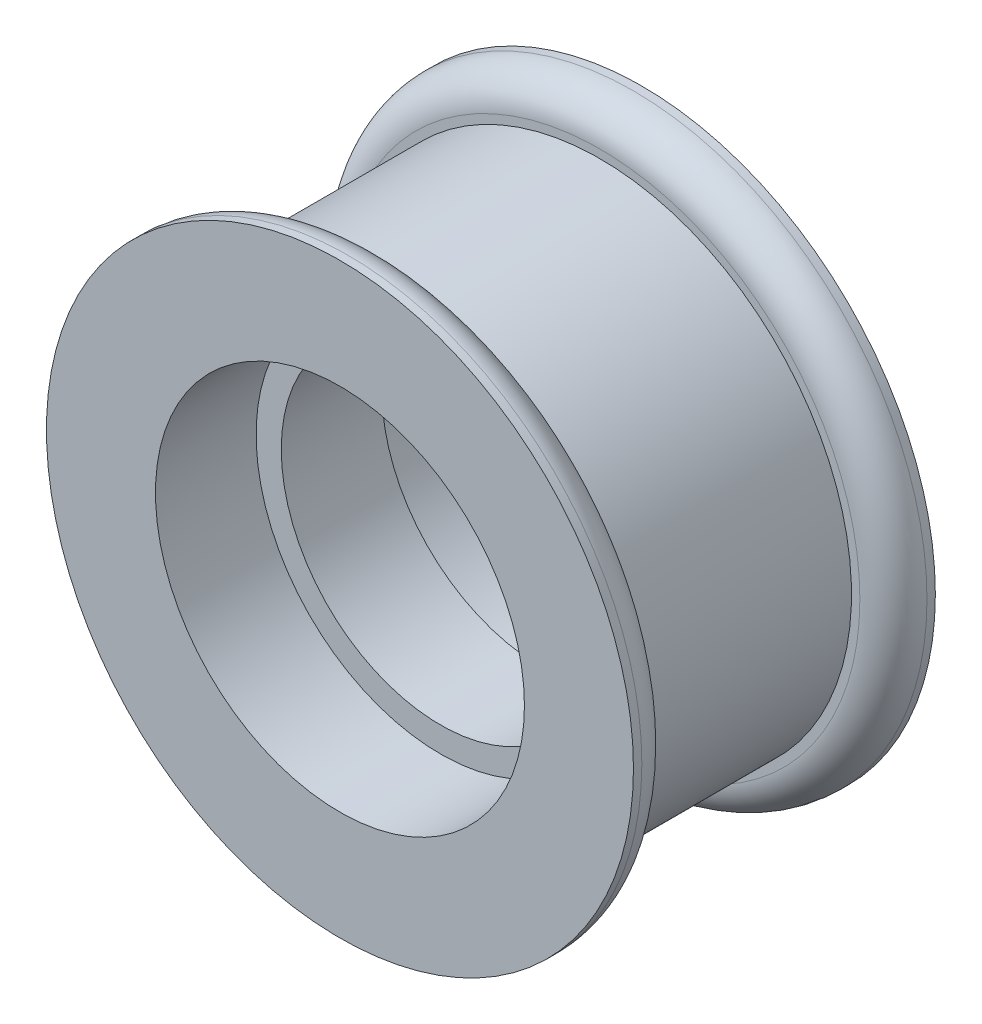
SolidWorks part; units mm, degrees
material "AISI 304"
ref_plane "前视基准面" through (0, 0, 0) normal (0, 0, 1) x (1, 0, 0)
ref_plane "上视基准面" through (0, 0, 0) normal (0, 1, 0) x (1, 0, 0)
ref_plane "右视基准面" through (0, 0, 0) normal (1, 0, 0) x (0, 0, -1)
sketch "草图1" plane through (0, 0, 0) normal (0, 0, 1) x (1, 0, 0)
  circle A0 centre (0, 0) radius 15
  dimension "D1" = 30
extrude "拉伸1" add sketch "草图1" along normal mid plane 13
sketch "草图2" plane through (0, 0, 6.5) normal (0, 0, 1) x (1, 0, 0)
  circle A0 centre (0, 0) radius 17.5
  dimension "D1" = 35
extrude "拉伸2" add sketch "草图2" along normal blind 2.5
mirror "镜向1" about plane through (0, 0, 0) normal (0, 0, 1) of "拉伸2"
sketch "草图3" plane through (0, 0, 9) normal (0, 0, 1) x (1, 0, 0)
  circle A0 centre (0, 0) radius 11
  dimension "D1" = 22
extrude "切除-拉伸1" cut sketch "草图3" against normal blind 6
sketch "草图4" plane through (0, 0, -9) normal (0, 0, -1) x (-1, 0, 0)
  circle A0 centre (0, 0) radius 11
  dimension "D1" = 22
extrude "切除-拉伸2" cut sketch "草图4" against normal blind 6
sketch "草图5" plane through (0, 0, -3) normal (0, 0, -1) x (-1, 0, 0)
  circle A0 centre (0, 0) radius 9.5
  dimension "D1" = 19
extrude "切除-拉伸3" cut sketch "草图5" against normal through all
fillet "圆角1" radius 2 2 edges at (17.5, 0, -6.5) (17.5, 0, 6.5)
